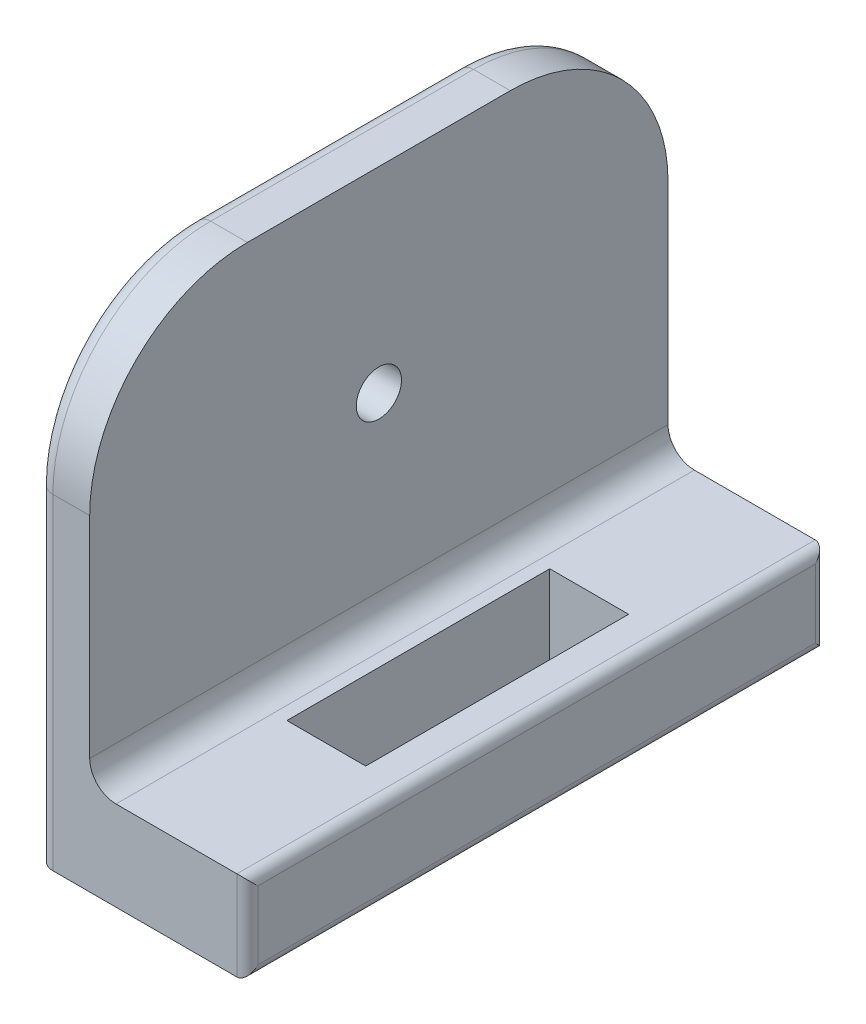
SolidWorks part; units mm, degrees
ref_plane "Front Plane" through (0, 0, 0) normal (0, 0, 1) x (1, 0, 0)
ref_plane "Top Plane" through (0, 0, 0) normal (0, 1, 0) x (1, 0, 0)
ref_plane "Right Plane" through (0, 0, 0) normal (1, 0, 0) x (0, 0, -1)
sketch "Sketch1" plane through (0, 0, 0) normal (0, 1, 0) x (1, 0, 0)
  line L1 (0, 0) -> (40, 0)
  line L2 (0, 0) -> (0, 110)
  line L3 (0, 110) -> (40, 110)
  line L4 (40, 0) -> (40, 110)
  dimension "D1" = 40
  dimension "D2" = 110
extrude "Boss-Extrude1" add sketch "Sketch1" along normal blind 17
sketch "Sketch4" plane through (0, 0, 0) normal (1, 0, 0) x (0, 0, -1)
  line L1 (0, 17) -> (110, 17)
  line L2 (0, 17) -> (0, 92)
  line L3 (0, 92) -> (110, 92)
  line L4 (110, 17) -> (110, 92)
  dimension "D1" = 75
extrude "Boss-Extrude2" add sketch "Sketch4" along normal blind 10
sketch "Sketch5" plane through (0, 17, 0) normal (0, 1, 0) x (1, 0, 0)
  line L0 (25, 0) -> (25, 30) construction
  line L1 (17.5, 80) -> (32.5, 80)
  line L2 (17.5, 80) -> (17.5, 30)
  line L3 (17.5, 30) -> (32.5, 30)
  line L4 (32.5, 80) -> (32.5, 30)
  line L5 (10, 0) -> (40, 0) construction
  line L6 (40, 55) -> (32.5, 55) construction
  line L7 (40, 0) -> (40, 110) construction
  dimension "D1" = 30
  dimension "D2" = 7.5
extrude "Cut-Extrude1" cut sketch "Sketch5" against normal up to surface (17 mm away) up to face at (20, 0, -55)
sketch "Sketch6" plane through (10, 0, 0) normal (1, 0, 0) x (0, 0, -1)
  line L0 (55, 17) -> (55, 54.7) construction
  line L1 (0, 17) -> (110, 17) construction
  circle A0 centre (55, 54.7) radius 4.3
  dimension "D2" = 8.6
  dimension "D1" = 37.7
extrude "Cut-Extrude2" cut sketch "Sketch6" against normal up to surface (10 mm away) up to face at (0, 46, -55)
fillet "Fillet1" radius 30 2 edges at (5, 92, 0) (5, 92, -110)
fillet "Fillet2" radius 3 5 edges at (0, 83.2132, -8.7868) (0, 92, -55) (0, 83.2132, -101.2132) (0, 31, 0) (0, 31, -110)
fillet "Fillet3" radius 5 1 edges at (10, 17, -55)
fillet "Fillet4" radius 2 4 edges at (40, 8.5, 0) (40, 17, -55) (40, 8.5, -110) (40, 0, -55)
